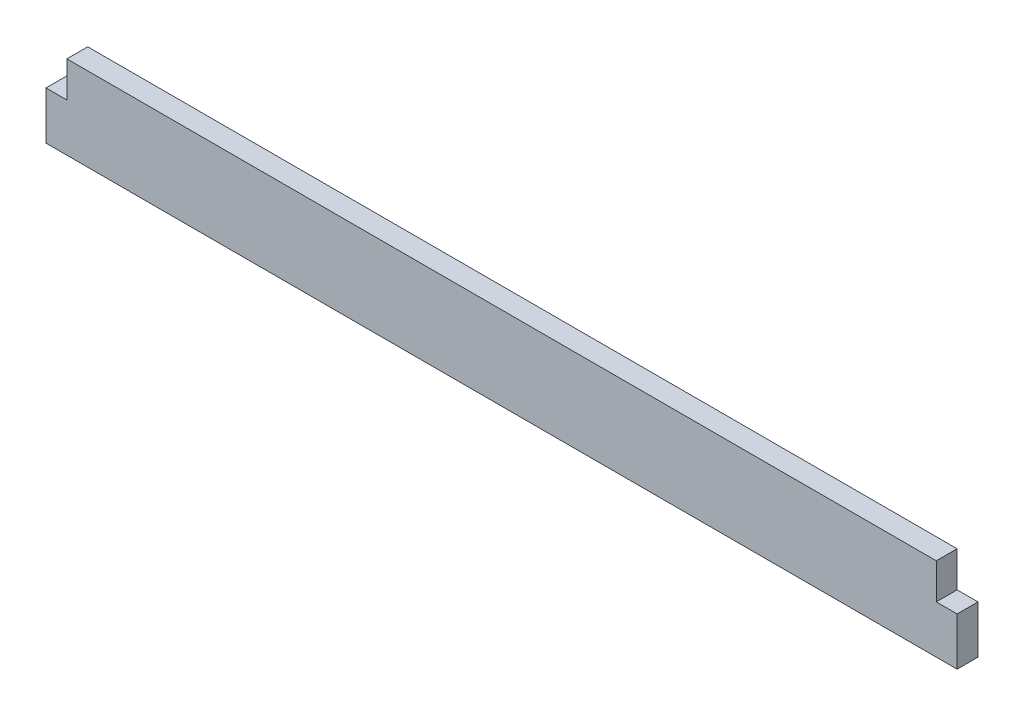
SolidWorks part; units mm, degrees
ref_plane "Front Plane" through (0, 0, 0) normal (0, 0, 1) x (1, 0, 0)
ref_plane "Top Plane" through (0, 0, 0) normal (0, 1, 0) x (1, 0, 0)
ref_plane "Right Plane" through (0, 0, 0) normal (1, 0, 0) x (0, 0, -1)
sketch "Sketch1" plane through (0, 0, 0) normal (0, 0, 1) x (1, 0, 0)
  line L8 (12, 12) -> (0, 12)
  line L10 (113, 12) -> (125, 12)
  line L12 (0, 12) -> (0, 6.8827)
  line L13 (0, 6.8827) -> (-3, 6.8827)
  line L14 (-3, 6.8827) -> (-3, 0)
  line L15 (-3, 0) -> (128, 0)
  line L21 (12, 12) -> (113, 12)
  line L24 (128, 0) -> (128, 6.8827)
  line L25 (128, 6.8827) -> (125, 6.8827)
  line L26 (125, 6.8827) -> (125, 12)
extrude "Boss-Extrude1" add sketch "Sketch1" along normal blind 3
